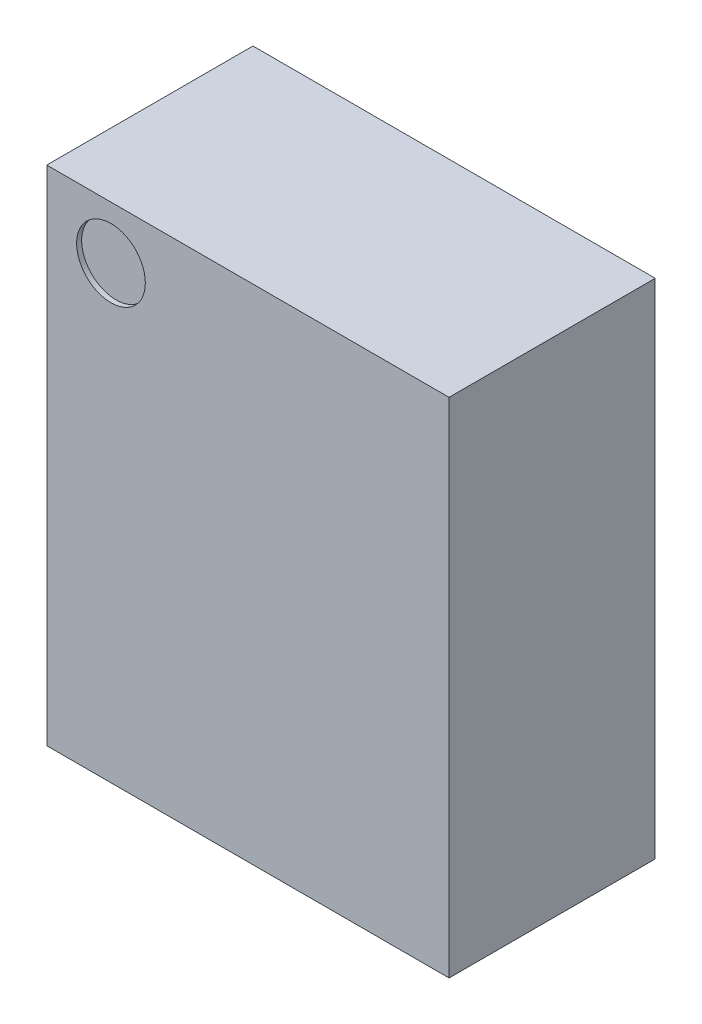
SolidWorks part; units mm, degrees
ref_plane "Front Plane" through (0, 0, 0) normal (0, 0, 1) x (1, 0, 0)
ref_plane "Top Plane" through (0, 0, 0) normal (0, 1, 0) x (1, 0, 0)
ref_plane "Right Plane" through (0, 0, 0) normal (1, 0, 0) x (0, 0, -1)
sketch "Sketch1" plane through (0, 0, 0) normal (0, 0, 1) x (1, 0, 0)
  line L1 (-0.8, -1) -> (0.8, -1)
  line L2 (-0.8, -1) -> (-0.8, 1)
  line L3 (-0.8, 1) -> (0.8, 1)
  line L4 (0.8, -1) -> (0.8, 1)
  line L5 (-0.8, -1) -> (0.8, 1) construction
  line L6 (-0.8, 1) -> (0.8, -1) construction
  point P0 (0, 0)
  dimension "D1" = 1.6
  dimension "D2" = 2
extrude "Boss-Extrude1" add sketch "Sketch1" along normal blind 0.82 contours L3 L4 L1 L2
sketch "Sketch2" plane through (0, 0, 0.82) normal (0, 0, 1) x (1, 0, 0)
  circle A0 centre (-0.5446, 0.7899) radius 0.1366
extrude "Cut-Extrude1" cut sketch "Sketch2" against normal blind 0.02
sketch "Sketch3" plane through (0, 0, 0.82) normal (0, 0, 1) x (1, 0, 0)
  line L0 (-0.8, 1) -> (0.8, 1) construction
  line L1 (0.2, 0.625) -> (0.75, 0.625)
  line L2 (0.2, 0.625) -> (0.2, 0.975)
  line L3 (0.2, 0.975) -> (0.75, 0.975)
  line L4 (0.75, 0.625) -> (0.75, 0.975)
  line L5 (0.8, -1) -> (0.8, 1) construction
  line L6 (-0.75, 0.625) -> (-0.75, 0.825)
  line L8 (-0.2, 0.625) -> (-0.2, 0.975)
  line L9 (-0.6, 0.975) -> (-0.2, 0.975)
  line L10 (-0.75, -0.975) -> (-0.75, -0.625)
  line L11 (-0.75, -0.975) -> (-0.2, -0.975)
  line L12 (-0.2, -0.975) -> (-0.2, -0.625)
  line L13 (-0.75, -0.625) -> (-0.2, -0.625)
  line L14 (0.2, -0.975) -> (0.2, -0.625)
  line L15 (0.2, -0.975) -> (0.75, -0.975)
  line L16 (0.75, -0.975) -> (0.75, -0.625)
  line L17 (0.2, -0.625) -> (0.75, -0.625)
  line L18 (-0.75, 0.625) -> (-0.75, 0.525)
  line L19 (-0.75, 0.525) -> (-0.2, 0.525)
  line L20 (-0.2, 0.525) -> (-0.2, 0.625)
  line L21 (-0.75, 0.825) -> (-0.6, 0.975)
  line L22 (-0.75, 0.625) -> (-0.2, 0.625) [skipped]
  line L23 (-0.8, -1) -> (-0.8, 1) construction
  point P4 (0.475, 0.625)
  point P7 (0, 1)
  point P10 (0.8, 0)
  point P11 (0.75, 0.8)
  dimension "D1" = 0.55
  dimension "D2" = 0.35
  dimension "D3" = 0.475
  dimension "D4" = 0.8
  dimension "D7" = 0.45
  dimension "D8" = 0.15
  dimension "D9" = 0.05
  dimension "D10" = 135
  dimension "D5" = 2
  dimension "D6" = 2
extrude "Boss-Extrude2" add sketch "Sketch3" against normal blind 0.02 from surface at -0.82 starting at face at (0, 0, 0)
